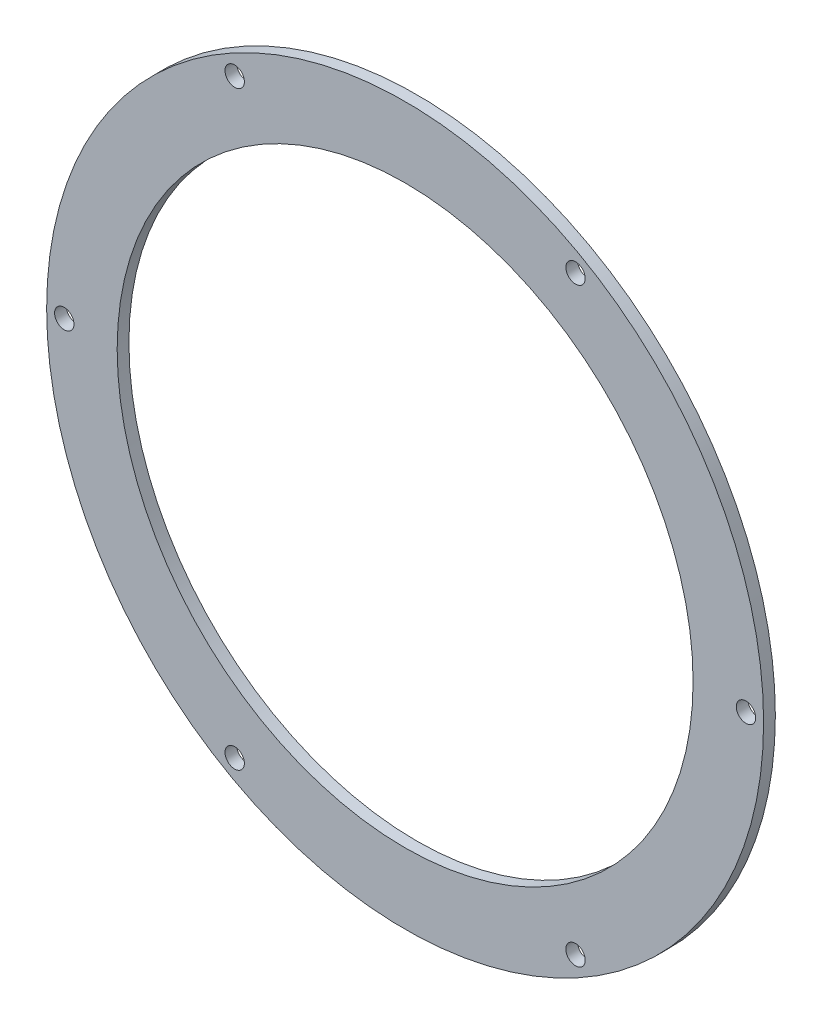
SolidWorks part; units mm, degrees
ref_plane "Спереди" through (0, 0, 0) normal (0, 0, 1) x (1, 0, 0)
ref_plane "Сверху" through (0, 0, 0) normal (0, 1, 0) x (1, 0, 0)
ref_plane "Справа" through (0, 0, 0) normal (1, 0, 0) x (0, 0, -1)
sketch "Эскиз1" plane through (0, 0, 0) normal (0, 0, 1) x (1, 0, 0)
  circle A0 centre (0, 0) radius 61
  circle A1 centre (0, 0) radius 49
extrude "Stator_clamp" add sketch "Эскиз1" along normal blind 2 from offset 20
sketch "Эскиз2" plane through (0, 0, 0) normal (0, 0, 1) x (1, 0, 0)
  circle A0 centre (58, 0) radius 1.65
  circle A1 centre (29, 50.2295) radius 1.65
  circle A2 centre (-29, 50.2295) radius 1.65
  circle A3 centre (-58, 0) radius 1.65
  circle A4 centre (-29, -50.2295) radius 1.65
  circle A5 centre (29, -50.2295) radius 1.65
extrude "Through_holes" cut sketch "Эскиз2" against normal mid plane 200
